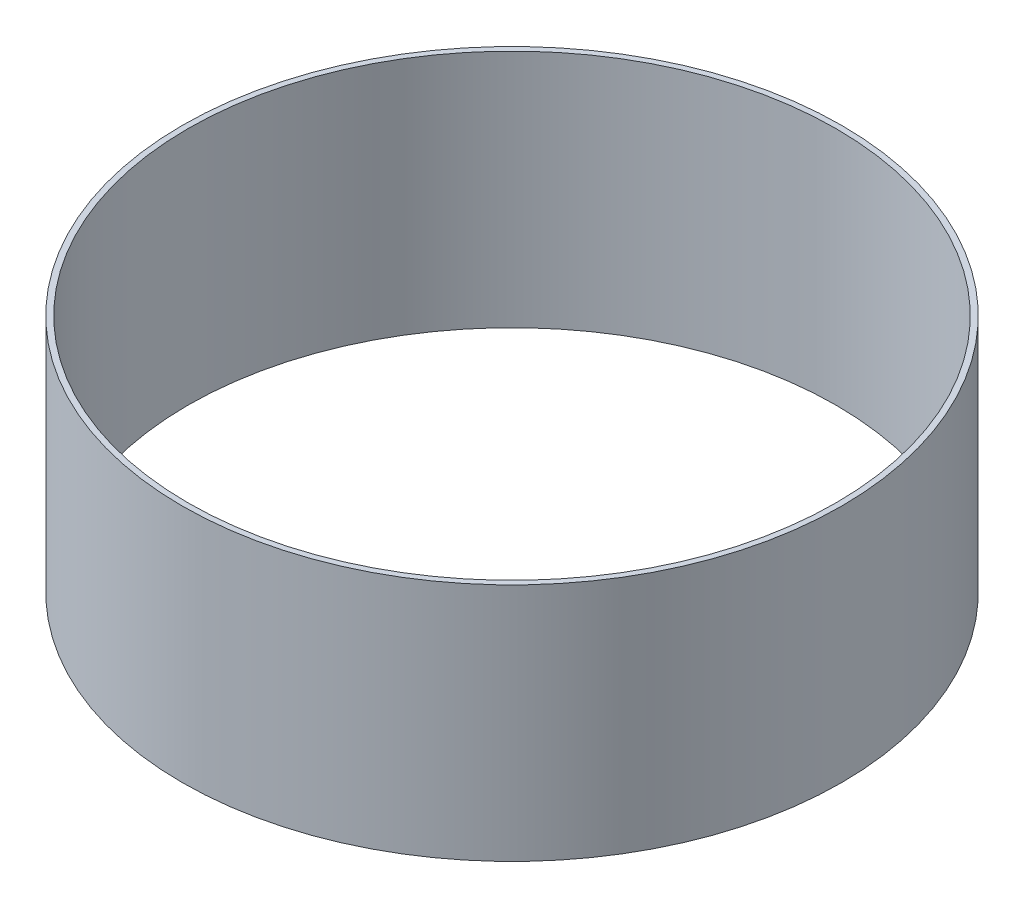
SolidWorks part; units mm, degrees
ref_plane "Front Plane" through (0, 0, 0) normal (0, 0, 1) x (1, 0, 0)
ref_plane "Top Plane" through (0, 0, 0) normal (0, 1, 0) x (1, 0, 0)
ref_plane "Right Plane" through (0, 0, 0) normal (1, 0, 0) x (0, 0, -1)
sketch "Sketch1" plane through (0, 0, 0) normal (0, 1, 0) x (1, 0, 0)
  circle A0 centre (0, 0) radius 46
  circle A1 centre (0, 0) radius 46.8
  dimension "D1" = 0.8
  dimension "D2" = 92
extrude "Boss-Extrude1" add sketch "Sketch1" along normal blind 34
